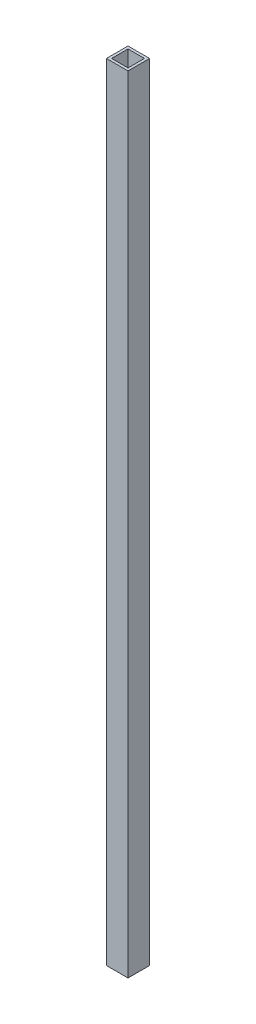
SolidWorks part; units mm, degrees
ref_plane "Front Plane" through (0, 0, 0) normal (0, 0, 1) x (1, 0, 0)
ref_plane "Top Plane" through (0, 0, 0) normal (0, 1, 0) x (1, 0, 0)
ref_plane "Right Plane" through (0, 0, 0) normal (1, 0, 0) x (0, 0, -1)
sketch "Sketch1" plane through (0, 0, 0) normal (0, 1, 0) x (1, 0, 0)
  line L1 (15.8767, 21.8352) -> (24.3767, 21.8352)
  line L2 (15.8767, 21.8352) -> (15.8767, 30.3352)
  line L3 (15.8767, 30.3352) -> (24.3767, 30.3352)
  line L4 (24.3767, 21.8352) -> (24.3767, 30.3352)
  line L5 (16.8767, 29.3352) -> (23.3767, 29.3352)
  line L6 (16.8767, 29.3352) -> (16.8767, 22.8352)
  line L7 (16.8767, 22.8352) -> (23.3767, 22.8352)
  line L8 (23.3767, 29.3352) -> (23.3767, 22.8352)
  dimension "D1" = 8.5
  dimension "D2" = 8.5
  dimension "D3" = 6.5
  dimension "D4" = 6.5
  dimension "D5" = 1
  dimension "D6" = 1
extrude "Boss-Extrude1" add sketch "Sketch1" along normal blind 310
